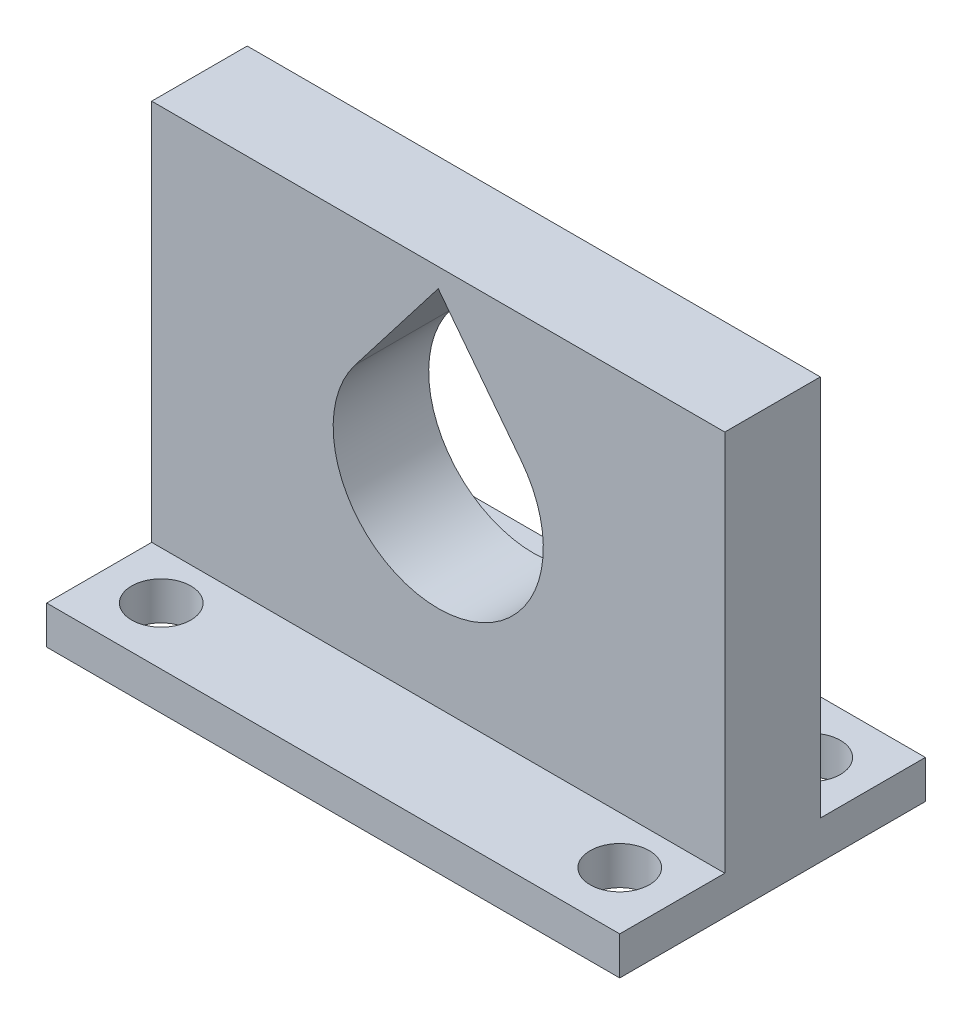
SolidWorks part; units mm, degrees
ref_plane "前视基准面" through (0, 0, 0) normal (0, 0, 1) x (1, 0, 0)
ref_plane "上视基准面" through (0, 0, 0) normal (0, 1, 0) x (1, 0, 0)
ref_plane "右视基准面" through (0, 0, 0) normal (1, 0, 0) x (0, 0, -1)
other "Configuration Table"
sketch "草图1" plane through (0, 0, 0) normal (0, 0, 1) x (1, 0, 0)
  line L0 (0, 0) -> (0, 10)
  line L1 (-15, -10) -> (15, -10)
  line L2 (-15, -10) -> (-15, 10)
  line L3 (-15, 10) -> (15, 10)
  line L4 (15, -10) -> (15, 10)
  line L5 (-15, -10) -> (15, 10) construction
  line L6 (-15, 10) -> (15, -10) construction
  line L7 (0, 8.1502) -> (-4.0446, 3.5778)
  line L8 (0, 8.1502) -> (4.0447, 3.5778)
  circle A0 centre (0, 0) radius 5.4
  dimension "D1" = 10.8
  dimension "D2" = 30
  dimension "D3" = 20
extrude "凸台-拉伸1" add sketch "草图1" along normal blind 5
sketch "草图2" plane through (0, -10, 0) normal (0, -1, 0) x (1, 0, 0)
  line L0 (0, 0) -> (0, 5)
  line L2 (-15, -5.5) -> (15, -5.5)
  line L3 (-15, -5.5) -> (-15, 10.5)
  line L4 (-15, 10.5) -> (15, 10.5)
  line L5 (15, -5.5) -> (15, 10.5)
  line L6 (-15, -5.5) -> (15, 10.5) construction
  line L7 (-15, 10.5) -> (15, -5.5) construction
  point P2 (0, 2.5)
  line M2 (-15, 0) -> (15, 0)
  line M3 (15, 0) -> (15, 5)
  line M4 (15, 5) -> (-15, 5)
  line M5 (-15, 5) -> (-15, 0)
  dimension "D1" = 16
extrude "凸台-拉伸3" add sketch "草图2" along normal blind 2 contours L2 L5 L3 M2 | L5 L4 L3 M4 | L0 M2 M4 M5 | L0 M2 M3 M4
sketch "草图4" plane through (0, -10, 0) normal (0, 1, 0) x (1, 0, 0)
  line L0 (-1015, -2.5) -> (48985, -2.5) construction
  line L1 (-15, 5.5) -> (-12, 5.5)
  line L2 (-15, 5.5) -> (-15, 2.5)
  line L3 (-15, 2.5) -> (-12, 2.5)
  line L4 (-12, 5.5) -> (-12, 2.5)
  line L5 (-15, -5) -> (-15, 0) construction
  line L6 (0, -994.5) -> (0, 49005.5) construction
  line L7 (-15, 5.5) -> (15, 5.5) construction
  circle A0 centre (-12, 2.5) radius 1.55
  circle A1 centre (12, 2.5) radius 1.55
  circle A2 centre (12, -7.5) radius 1.55
  circle A3 centre (-12, -7.5) radius 1.55
  point P11 (-15, -2.5)
  point P16 (0, 5.5)
  dimension "D3" = 3.1
  dimension "D1" = 3
  dimension "D2" = 3
extrude "切除-拉伸1" cut sketch "草图4" against normal blind 2 contours L3 A0 L4 | L4 A0 L3 | A1 | A2 | A3
sketch "草图7" plane through (0, 0, 0) normal (0, 0, -1) x (-1, 0, 0)
  line L0 (0, 0) -> (0, 9)
  line L1 (0, 9) -> (-4.3266, 3.3957)
  line L2 (0, 9) -> (4.3535, 3.3611)
  circle A0 centre (0, 0) radius 5.5
  arc M6 (4.0446, 3.5778) -> (-4.0447, 3.5778) centre (0, 0) cw
  line M7 (-4.0447, 3.5778) -> (0, 8.1502)
  line M8 (0, 8.1502) -> (4.0446, 3.5778)
  dimension "D1" = 11
  dimension "D2" = 9
extrude "切除-拉伸7" cut sketch "草图7" against normal blind 10 contours A0 L0 L1 M7 | A0 L2 L0 M8 | A0 M8 M6 M7
